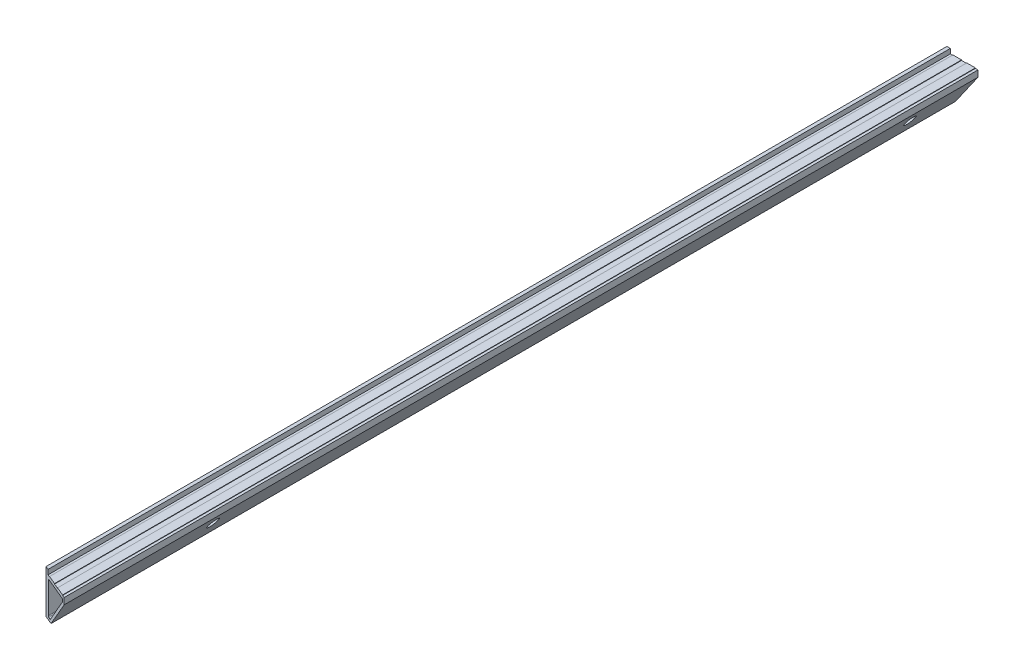
SolidWorks part; units mm, degrees
ref_plane "前视基准面" through (0, 0, 0) normal (0, 0, 1) x (1, 0, 0)
ref_plane "上视基准面" through (0, 0, 0) normal (0, 1, 0) x (1, 0, 0)
ref_plane "右视基准面" through (0, 0, 0) normal (1, 0, 0) x (0, 0, -1)
sketch "草图1" plane through (0, 0, 0) normal (0, 0, 1) x (1, 0, 0)
  line L0 (36, -0.5) -> (36, -7.8426)
  line L1 (7, 0) -> (17, 0)
  line L2 (0, 0) -> (0, -45)
  line L3 (0, -45) -> (10, -45)
  line L4 (36, -7.8426) -> (10, -45)
  line L5 (0, 0) -> (0, 5)
  line L7 (33, -5) -> (33, -6.5821)
  line L8 (32.8193, -7.1554) -> (8.7362, -41.5733)
  line L9 (5.5, -42) -> (7.9169, -42)
  line L10 (33, -3) -> (33, -6.8973) construction
  line L11 (5.5, -4) -> (32, -4)
  line L12 (3, -42) -> (8.4377, -42) construction
  line L14 (4, -0.5) -> (4, 5)
  line L15 (4.5, -5) -> (4.5, -41)
  line L16 (0, 0) -> (36, 0) construction
  line L17 (3, -3) -> (33, -3) construction
  line L18 (3, -3) -> (3, -42) construction
  line L22 (0, 5) -> (4, 5)
  line L23 (4, -0.5) -> (7, -0.5)
  line L24 (33, -6.8973) -> (8.4377, -42) construction
  line L25 (33, -0.5) -> (33, 0)
  line L26 (23, -0.5) -> (23, 0)
  line L27 (17, -0.5) -> (17, 0)
  line L28 (7, -0.5) -> (7, 0)
  line L29 (7, 0) -> (7, 8.4394) construction
  line L30 (33, 0) -> (33, 8.4394) construction
  line L31 (35.5, -0.5) -> (35.5, -7.6851) construction
  line L32 (35.5, -7.6851) -> (9.7396, -44.5) construction
  line L33 (0.5, 0) -> (0.5, 4.5) construction
  line L34 (3.5, -0.5) -> (3.5, 4.5) construction
  line L35 (0.5, 0) -> (0.5, -44.5) construction
  line L36 (0.5, 4.5) -> (3.5, 4.5) construction
  line L37 (0.5, -44.5) -> (9.7396, -44.5) construction
  line L38 (23, 0) -> (23, 8.4394) construction
  line L39 (17, 0) -> (17, 8.4394) construction
  line L40 (4, 0) -> (36, 0) construction
  line L41 (3.5, -0.5) -> (35.5, -0.5) construction
  line L42 (4, 0) -> (4, 5) construction
  line L43 (23, 0) -> (33, 0)
  line L44 (17, -0.5) -> (23, -0.5)
  line L45 (33, -0.5) -> (36, -0.5)
  line L46 (36, 0) -> (36, -7.8426) construction
  arc A0 (8.7362, -41.5733) -> (7.9169, -42) centre (7.9169, -41) cw
  arc A1 (4.5, -41) -> (5.5, -42) centre (5.5, -41) ccw
  arc A2 (33, -6.5821) -> (32.8193, -7.1554) centre (32, -6.5821) cw
  arc A3 (33, -5) -> (32, -4) centre (32, -5) ccw
  arc A4 (5.5, -4) -> (4.5, -5) centre (5.5, -5) ccw
  dimension "D3" = 1
  dimension "D15" = 4.5
  dimension "D2" = 45
  dimension "D4" = 10
  dimension "D5" = 5
  dimension "D9" = 0.5
  dimension "D10" = 32
  dimension "D14" = 3
  dimension "D7" = 4
  dimension "D16" = 34.981
  dimension "D6" = 3
  dimension "D8" = 4
  dimension "D11" = 10
  dimension "D12" = 6
  dimension "D13" = 10
extrude "凸台-拉伸1" add sketch "草图1" along normal blind 1056
hole_wizard "Ø7.0 (7) 直径孔1" positions "草图3" profile "草图2" hole size "Ø7.0" standard "GB" end condition through all
sketch "草图3" plane through (0, 0, 0) normal (-1, 0, 0) x (0, 0, 1)
  line L0 (0, 5) -> (0, -45) construction
  line L1 (1056, 5) -> (0, 5) construction
  line L2 (1056, 5) -> (1056, -45) construction
  point P0 (68.68, -22)
  point P1 (874, -22)
  dimension "D1" = 68.68
  dimension "D2" = 182
  dimension "D3" = 27
sketch "草图2" plane through (0, -22, 68.68) normal (0, 1, 0) x (0, 0, 1)
  line L0 (0, 0) -> (0, 36)
  line L1 (0, 36) -> (3.5, 36)
  line L2 (3.5, 36) -> (3.5, 0)
  line L5 (3.5, 0) -> (0, 0)
  line L11 (0, -6.35) -> (0, 107.95) construction
  dimension "通孔孔直径" = 7
  dimension "通孔孔深度" = 36
sketch "草图5" plane through (36, 0, 0) normal (1, 0, 0) x (0, 0, -1)
  line L4 (-68.68, -13.8215) -> (-68.68, -30.3235) construction
  circle A0 centre (-68.68, -22.0725) radius 6
  circle A1 centre (-874, -22) radius 6
  dimension "D1" = 12
  dimension "D2" = 12
extrude "切除-拉伸2" cut sketch "草图5" against normal up to surface (13.5678 mm away)
hole_wizard "M5 螺纹孔1" positions "草图7" profile "草图6" tap size "M5" standard "GB"
sketch "草图7" plane through (0, 0, 0) normal (-1, 0, 0) x (0, 0, 1)
  point P0 (18.6366, -11.936)
  point P1 (18.6366, -32)
  point P3 (118.6756, -11.936)
  point P5 (118.6756, -32)
sketch "草图6" plane through (0, -11.936, 18.6366) normal (0, 1, 0) x (0, 0, 1)
  line L0 (0, 0) -> (0, 4.5)
  line L1 (0, 4.5) -> (2.5, 4.5)
  line L2 (2.5, 4.5) -> (2.5, 0)
  line L5 (2.5, 0) -> (0, 0)
  line L11 (0, -6.35) -> (0, 107.95) construction
  dimension "螺纹线主直径" = 5
  dimension "通孔螺纹孔钻头深度" = 4.5
hole_wizard "M5 螺纹孔2" positions "草图9" profile "草图8" tap size "M5" standard "GB"
sketch "草图9" plane through (0, 0, 0) normal (-1, 0, 0) x (0, 0, 1)
  line L0 (874, -3.198) -> (874, -40.753) construction
  line L2 (859.6802, -22) -> (928.2498, -22) construction
  point P0 (850, -12)
  point P1 (898, -12)
  point P3 (898, -32)
  point P5 (850, -32)
  dimension "D1" = 20
  dimension "D2" = 48
sketch "草图8" plane through (0, -12, 850) normal (0, 1, 0) x (0, 0, 1)
  line L0 (0, 0) -> (0, 4.5)
  line L1 (0, 4.5) -> (2.5, 4.5)
  line L2 (2.5, 4.5) -> (2.5, 0)
  line L5 (2.5, 0) -> (0, 0)
  line L11 (0, -6.35) -> (0, 107.95) construction
  dimension "螺纹线主直径" = 5
  dimension "通孔螺纹孔钻头深度" = 4.5
sketch "草图11" plane through (0, 5, 0) normal (0, 1, 0) x (1, 0, 0)
  line L0 (36, -1056) -> (0, -1040.9409)
  line L1 (0, -1056) -> (36, -1056)
  line L2 (0, -1056) -> (0, -1040.9409)
  line L3 (0, -1056) -> (0, 0) construction
  dimension "D1" = 22.7
extrude "切除-拉伸3" cut sketch "草图11" against normal through all
